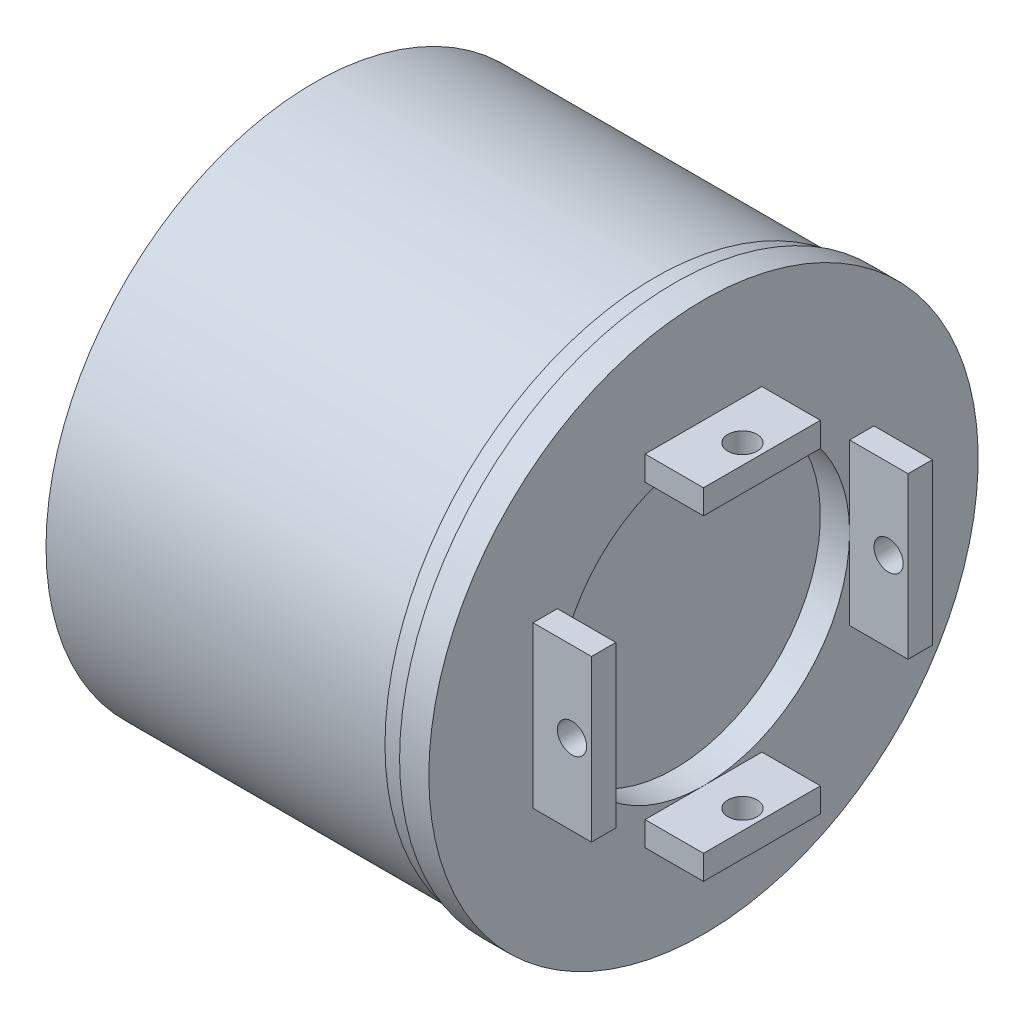
SolidWorks part; units mm, degrees
ref_plane "前视基准面" through (0, 0, 0) normal (0, 0, 1) x (1, 0, 0)
ref_plane "上视基准面" through (0, 0, 0) normal (0, 1, 0) x (1, 0, 0)
ref_plane "右视基准面" through (0, 0, 0) normal (1, 0, 0) x (0, 0, -1)
other "Configuration Table"
sketch "草图1" plane through (0, 0, 0) normal (0, 0, 1) x (1, 0, 0)
  line L0 (-20.3654, 0) -> (66.6441, 0) construction
  line L1 (1.5, 16.5) -> (0, 16.5)
  line L2 (0, 16.5) -> (0, 16.4)
  line L3 (0, 16.4) -> (-2.2, 16.4)
  line L4 (-2.2, 16.4) -> (-2.2, 0)
  line L5 (1.5, 16.5) -> (1.5, 21.5)
  line L6 (1.5, 21.5) -> (1, 21.5)
  line L7 (1, 21.5) -> (1, 27.5)
  line L8 (1, 27.5) -> (36, 27.5)
  line L9 (36, 27.5) -> (36, 27.7)
  line L10 (36, 27.7) -> (38, 27.7)
  line L11 (38, 27.7) -> (38, 28.2)
  line L12 (38, 28.2) -> (41, 28.2)
  line L13 (41, 28.2) -> (41, 15)
  line L14 (41, 15) -> (38, 15)
  line L15 (38, 15) -> (38, 0)
  line L16 (-2.2, 0) -> (38, 0)
  point P16 (66.6441, 0)
  point P20 (38, 0)
  dimension "D1" = 1.5
  dimension "D2" = 0.5
  dimension "D3" = 35
  dimension "D4" = 27.5
  dimension "D5" = 6
  dimension "D6" = 5
  dimension "D7" = 0.1
  dimension "D8" = 2.2
  dimension "D9" = 0.2
  dimension "D10" = 0.5
  dimension "D11" = 2
  dimension "D12" = 3
  dimension "D13" = 3
  dimension "D14" = 15
revolve "旋转1" add sketch "草图1" angle 360 about L0
sketch "草图2" plane through (1, 0, 0) normal (-1, 0, 0) x (0, 0, 1)
  line L0 (0, 33.7454) -> (0, -37.949) construction
  circle A0 centre (0, 25) radius 1.5
  circle A1 centre (0, 0) radius 25 construction
  circle A2 centre (21.6506, -12.5) radius 1.5
  circle A3 centre (-21.6506, -12.5) radius 1.5
  point P13 (0, 0)
  dimension "D1" = 3
  dimension "D2" = 50
  dimension "D3" = 3
extrude "切除-拉伸1" cut sketch "草图2" against normal blind 8
sketch "草图3" plane through (41, 0, 0) normal (1, 0, 0) x (0, 0, -1)
  line L0 (0, 42.1526) -> (0, -46.7454) construction
  line L1 (-45.0717, 0) -> (44.2933, 0) construction
  line L2 (15, 8.25) -> (15, -8.25)
  line L3 (15, 8.25) -> (17.5, 8.25)
  line L4 (17.5, 8.25) -> (17.5, -8.25)
  line L5 (15, -8.25) -> (17.5, -8.25)
  line L6 (-6, 15) -> (6, 15)
  line L7 (6, 15) -> (6, 17.5)
  line L8 (6, 17.5) -> (-6, 17.5)
  line L9 (-6, 15) -> (-6, 17.5)
  line L10 (-15, 8.25) -> (-17.5, 8.25)
  line L11 (-15, 8.25) -> (-15, -8.25)
  line L12 (-15, -8.25) -> (-17.5, -8.25)
  line L13 (-17.5, 8.25) -> (-17.5, -8.25)
  line L14 (-6, -15) -> (-6, -17.5)
  line L15 (6, -17.5) -> (-6, -17.5)
  line L16 (6, -15) -> (6, -17.5)
  line L17 (-6, -15) -> (6, -15)
  circle A0 centre (0, 0) radius 15 construction
  point P12 (17.5, 0)
  point P13 (15, 0)
  point P18 (0, 15)
  point P19 (0, 17.5)
  dimension "D1" = 2.5
  dimension "D2" = 16.5
  dimension "D3" = 12
  dimension "D4" = 2.5
extrude "凸台-拉伸1" add sketch "草图3" along normal blind 6
sketch "草图4" plane through (0, 0, 0) normal (0, 0, 1) x (1, 0, 0)
  line L0 (-9.3593, 0) -> (56.8622, 0) construction
  line L1 (47, 8.25) -> (47, -8.25) construction
  circle A0 centre (45, 0) radius 1.5
  dimension "D1" = 3
  dimension "D2" = 2
extrude "切除-拉伸2" cut sketch "草图4" against normal mid plane 100
ref_axis "基准轴1" through (36, 0, 0) along (-1, 0, 0)
pattern_circular "阵列(圆周)1" count 2 over 90 about axis through (36, 0, 0) along (-1, 0, 0) of "切除-拉伸2"
